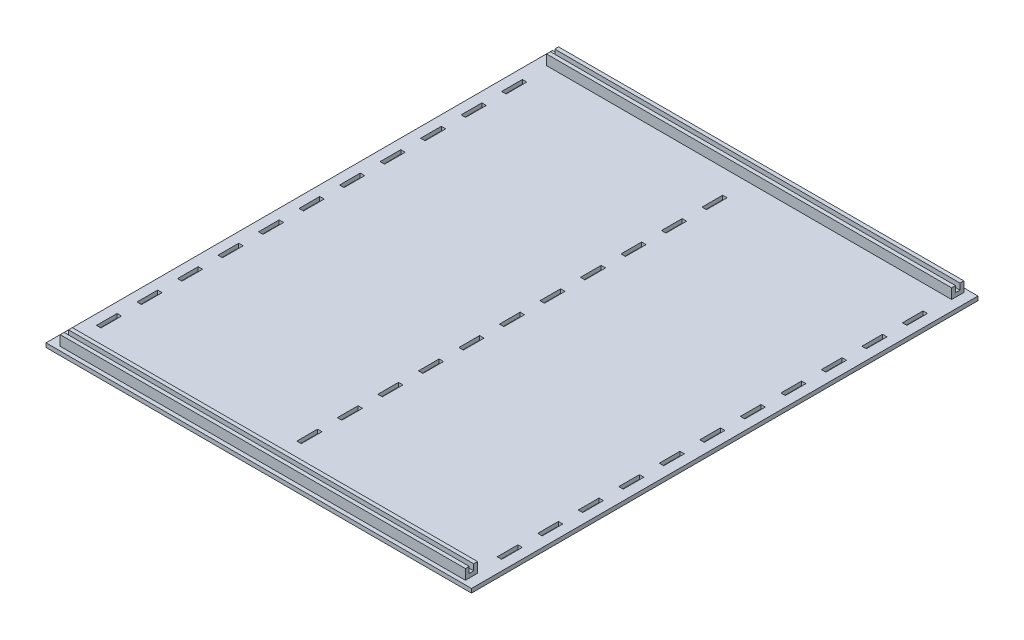
SolidWorks part; units mm, degrees
other "标注1"
sketch "草图3"
ref_plane "Front Plane" through (0, 0, 0) normal (0, 0, 1) x (1, 0, 0)
ref_plane "Top Plane" through (0, 0, 0) normal (0, 1, 0) x (1, 0, 0)
ref_plane "Right Plane" through (0, 0, 0) normal (1, 0, 0) x (0, 0, -1)
sketch "Sketch1" plane through (0, 0, 0) normal (0, 1, 0) x (1, 0, 0)
  line L1 (105, -125) -> (-105, -125)
  line L2 (105, -125) -> (105, 125)
  line L3 (105, 125) -> (-105, 125)
  line L4 (-105, -125) -> (-105, 125)
  line L5 (105, -125) -> (-105, 125) construction
  line L6 (105, 125) -> (-105, -125) construction
  point P0 (0, 0)
  dimension "D1" = 210
  dimension "D2" = 250
extrude "Boss-Extrude1" add sketch "Sketch1" along normal blind 2
sketch "Sketch2" plane through (0, 2, 0) normal (0, 1, 0) x (1, 0, 0)
  line L0 (-100, -123) -> (100, -123)
  line L1 (-105, -125) -> (105, -125) construction
  line L2 (-105, 125) -> (-105, -125) construction
  line L3 (105, -125) -> (105, 125) construction
  line L5 (-100, -123) -> (100, -123)
  line L6 (-100, -123) -> (-100, -117)
  line L7 (-100, -117) -> (100, -117)
  line L8 (100, -123) -> (100, -117)
  dimension "D1" = 2
  dimension "D2" = 5
  dimension "D3" = 5
  dimension "D4" = 6
extrude "Boss-Extrude2" add sketch "Sketch2" along normal blind 5 contours L0 L8 L7 L6
sketch "Sketch5" plane through (0, 7, 0) normal (0, 1, 0) x (1, 0, 0)
  line L1 (-100, -117) -> (100, -117) construction
  line L4 (-100, -118.9) -> (100, -118.9)
  line L5 (-100, -118.9) -> (-100, -121.1)
  line L6 (-100, -121.1) -> (100, -121.1)
  line L7 (100, -118.9) -> (100, -121.1)
  line L8 (-100, -123) -> (-100, -117) construction
  line L9 (100, -123) -> (100, -117) construction
  dimension "D1" = 2.2
  dimension "D2" = 1.9
extrude "Cut-Extrude1" cut sketch "Sketch5" against normal blind 3 contours L5 L4 L7 L6
sketch "Sketch6" plane through (0, 2, 0) normal (0, 1, 0) x (1, 0, 0)
  line L0 (105, 125) -> (-105, 125) construction
  line L1 (-100, 123) -> (100, 123)
  line L2 (-100, 123) -> (-100, 117)
  line L3 (-100, 117) -> (100, 117)
  line L4 (100, 123) -> (100, 117)
  line L5 (105, -125) -> (105, 125) construction
  line L6 (-105, 125) -> (-105, -125) construction
  dimension "D1" = 2
  dimension "D2" = 5
  dimension "D3" = 5
  dimension "D4" = 6
extrude "Boss-Extrude3" add sketch "Sketch6" along normal blind 5 contours L2 L1 L4 L3
sketch "Sketch7" plane through (0, 7, 0) normal (0, 1, 0) x (1, 0, 0)
  line L0 (-100, 123) -> (100, 123)
  line L1 (-100, 123) -> (-100, 117) construction
  line L3 (100, 123) -> (100, 117) construction
  line L4 (100, 121.1) -> (-100, 121.1)
  line L5 (100, 121.1) -> (100, 118.9)
  line L6 (100, 118.9) -> (-100, 118.9)
  line L7 (-100, 121.1) -> (-100, 118.9)
  line L8 (100, 121.1) -> (-100, 118.9) construction
  line L9 (100, 118.9) -> (-100, 121.1) construction
  point P8 (0, 120)
  line M7 (100, 117) -> (100, 123)
  line M9 (-100, 123) -> (-100, 117)
  dimension "D1" = 2.2
  dimension "D2" = 1.9
extrude "Cut-Extrude2" cut sketch "Sketch7" against normal blind 3 contours L6 L4 M7 M9
sketch "草图2" plane through (0, 2, 0) normal (0, 1, 0) x (1, 0, 0)
  line L0 (1.1, -14.9) -> (1.1, -25.1)
  line L1 (1.1, 5.1) -> (-1.1, 5.1)
  line L2 (1.1, 5.1) -> (1.1, -5.1)
  line L3 (1.1, -5.1) -> (-1.1, -5.1)
  line L4 (-1.1, 5.1) -> (-1.1, -5.1)
  line L5 (1.1, 5.1) -> (-1.1, -5.1) construction
  line L6 (1.1, -5.1) -> (-1.1, 5.1) construction
  line L7 (1.1, 25.1) -> (1.1, 14.9)
  line L8 (1.1, -14.9) -> (-1.1, -14.9)
  line L9 (1.1, 25.1) -> (-1.1, 25.1)
  line L10 (-1.1, 25.1) -> (-1.1, 14.9)
  line L11 (1.1, 14.9) -> (-1.1, 14.9)
  line L12 (1.1, 45.1) -> (1.1, 34.9)
  line L13 (1.1, 45.1) -> (-1.1, 45.1)
  line L14 (-1.1, 45.1) -> (-1.1, 34.9)
  line L15 (1.1, 34.9) -> (-1.1, 34.9)
  line L16 (1.1, 65.1) -> (1.1, 54.9)
  line L17 (1.1, 65.1) -> (-1.1, 65.1)
  line L18 (-1.1, 65.1) -> (-1.1, 54.9)
  line L19 (1.1, 54.9) -> (-1.1, 54.9)
  line L20 (1.1, 85.1) -> (1.1, 74.9)
  line L21 (1.1, 85.1) -> (-1.1, 85.1)
  line L22 (-1.1, 85.1) -> (-1.1, 74.9)
  line L23 (1.1, 74.9) -> (-1.1, 74.9)
  line L24 (1.1, 105.1) -> (1.1, 94.9)
  line L25 (1.1, 105.1) -> (-1.1, 105.1)
  line L26 (-1.1, 105.1) -> (-1.1, 94.9)
  line L27 (1.1, 94.9) -> (-1.1, 94.9)
  line L28 (-1.1, -14.9) -> (-1.1, -25.1)
  line L29 (1.1, -25.1) -> (-1.1, -25.1)
  line L30 (1.1, -34.9) -> (1.1, -45.1)
  line L31 (1.1, -34.9) -> (-1.1, -34.9)
  line L32 (-1.1, -34.9) -> (-1.1, -45.1)
  line L33 (1.1, -45.1) -> (-1.1, -45.1)
  line L34 (1.1, -54.9) -> (1.1, -65.1)
  line L35 (1.1, -54.9) -> (-1.1, -54.9)
  line L36 (-1.1, -54.9) -> (-1.1, -65.1)
  line L37 (1.1, -65.1) -> (-1.1, -65.1)
  line L38 (1.1, -74.9) -> (1.1, -85.1)
  line L39 (1.1, -74.9) -> (-1.1, -74.9)
  line L40 (-1.1, -74.9) -> (-1.1, -85.1)
  line L41 (1.1, -85.1) -> (-1.1, -85.1)
  line L42 (1.1, -94.9) -> (1.1, -105.1)
  line L43 (1.1, -94.9) -> (-1.1, -94.9)
  line L44 (-1.1, -94.9) -> (-1.1, -105.1)
  line L45 (1.1, -105.1) -> (-1.1, -105.1)
  line L46 (97.8, -5.1) -> (100, -5.1)
  line L47 (100, 5.1) -> (100, -5.1)
  line L48 (97.8, 5.1) -> (100, 5.1)
  line L49 (97.8, 5.1) -> (97.8, -5.1)
  line L50 (97.8, 14.9) -> (100, 14.9)
  line L51 (-97.8, 5.1) -> (-97.8, -5.1)
  line L52 (-97.8, 5.1) -> (-100, 5.1)
  line L53 (-100, 5.1) -> (-100, -5.1)
  line L54 (-97.8, -5.1) -> (-100, -5.1)
  line L55 (100, 25.1) -> (100, 14.9)
  line L56 (97.8, 25.1) -> (100, 25.1)
  line L57 (97.8, 25.1) -> (97.8, 14.9)
  line L58 (97.8, 34.9) -> (100, 34.9)
  line L59 (100, 45.1) -> (100, 34.9)
  line L60 (97.8, 45.1) -> (100, 45.1)
  line L61 (97.8, 45.1) -> (97.8, 34.9)
  line L62 (97.8, 54.9) -> (100, 54.9)
  line L63 (100, 65.1) -> (100, 54.9)
  line L64 (97.8, 65.1) -> (100, 65.1)
  line L65 (97.8, 65.1) -> (97.8, 54.9)
  line L66 (97.8, 74.9) -> (100, 74.9)
  line L67 (100, 85.1) -> (100, 74.9)
  line L68 (97.8, 85.1) -> (100, 85.1)
  line L69 (97.8, 85.1) -> (97.8, 74.9)
  line L70 (97.8, 94.9) -> (100, 94.9)
  line L71 (100, 105.1) -> (100, 94.9)
  line L72 (97.8, 105.1) -> (100, 105.1)
  line L73 (97.8, 105.1) -> (97.8, 94.9)
  line L74 (97.8, -5.1) -> (97.8, 14.9) construction
  line L75 (97.8, -25.1) -> (100, -25.1)
  line L76 (100, -14.9) -> (100, -25.1)
  line L77 (97.8, -14.9) -> (100, -14.9)
  line L78 (97.8, -14.9) -> (97.8, -25.1)
  line L79 (97.8, -45.1) -> (100, -45.1)
  line L80 (100, -34.9) -> (100, -45.1)
  line L81 (97.8, -34.9) -> (100, -34.9)
  line L82 (97.8, -34.9) -> (97.8, -45.1)
  line L83 (97.8, -65.1) -> (100, -65.1)
  line L84 (100, -54.9) -> (100, -65.1)
  line L85 (97.8, -54.9) -> (100, -54.9)
  line L86 (97.8, -54.9) -> (97.8, -65.1)
  line L87 (97.8, -85.1) -> (100, -85.1)
  line L88 (100, -74.9) -> (100, -85.1)
  line L89 (97.8, -74.9) -> (100, -74.9)
  line L90 (97.8, -74.9) -> (97.8, -85.1)
  line L91 (97.8, -105.1) -> (100, -105.1)
  line L92 (100, -94.9) -> (100, -105.1)
  line L93 (97.8, -94.9) -> (100, -94.9)
  line L94 (97.8, -94.9) -> (97.8, -105.1)
  line L95 (-100, 25.1) -> (-100, 14.9)
  line L96 (-97.8, 25.1) -> (-97.8, 14.9)
  line L97 (-97.8, 14.9) -> (-100, 14.9)
  line L98 (-97.8, 25.1) -> (-100, 25.1)
  line L99 (-100, 45.1) -> (-100, 34.9)
  line L100 (-97.8, 45.1) -> (-97.8, 34.9)
  line L101 (-97.8, 34.9) -> (-100, 34.9)
  line L102 (-97.8, 45.1) -> (-100, 45.1)
  line L103 (-100, 65.1) -> (-100, 54.9)
  line L104 (-97.8, 65.1) -> (-97.8, 54.9)
  line L105 (-97.8, 54.9) -> (-100, 54.9)
  line L106 (-97.8, 65.1) -> (-100, 65.1)
  line L107 (-100, 85.1) -> (-100, 74.9)
  line L108 (-97.8, 85.1) -> (-97.8, 74.9)
  line L109 (-97.8, 74.9) -> (-100, 74.9)
  line L110 (-97.8, 85.1) -> (-100, 85.1)
  line L111 (-100, 105.1) -> (-100, 94.9)
  line L112 (-97.8, 105.1) -> (-97.8, 94.9)
  line L113 (-97.8, 94.9) -> (-100, 94.9)
  line L114 (-97.8, 105.1) -> (-100, 105.1)
  line L115 (-97.8, -14.9) -> (-97.8, -25.1)
  line L116 (-97.8, -25.1) -> (-100, -25.1)
  line L117 (-100, -14.9) -> (-100, -25.1)
  line L118 (-97.8, -14.9) -> (-100, -14.9)
  line L119 (-97.8, -34.9) -> (-97.8, -45.1)
  line L120 (-97.8, -45.1) -> (-100, -45.1)
  line L121 (-100, -34.9) -> (-100, -45.1)
  line L122 (-97.8, -34.9) -> (-100, -34.9)
  line L123 (-97.8, -54.9) -> (-97.8, -65.1)
  line L124 (-97.8, -65.1) -> (-100, -65.1)
  line L125 (-100, -54.9) -> (-100, -65.1)
  line L126 (-97.8, -54.9) -> (-100, -54.9)
  line L127 (-97.8, -74.9) -> (-97.8, -85.1)
  line L128 (-97.8, -85.1) -> (-100, -85.1)
  line L129 (-100, -74.9) -> (-100, -85.1)
  line L130 (-97.8, -74.9) -> (-100, -74.9)
  line L131 (-97.8, -94.9) -> (-97.8, -105.1)
  line L132 (-97.8, -105.1) -> (-100, -105.1)
  line L133 (-100, -94.9) -> (-100, -105.1)
  line L134 (-97.8, -94.9) -> (-100, -94.9)
  point P0 (0, 0)
  dimension "D1" = 6
  dimension "D2" = 2.2
  dimension "D3" = 6
  dimension "D5" = 6
  dimension "D4" = 6
  dimension "D6" = 6
  dimension "D7" = 6
extrude "切除-拉伸3" cut sketch "草图2" against normal through all
